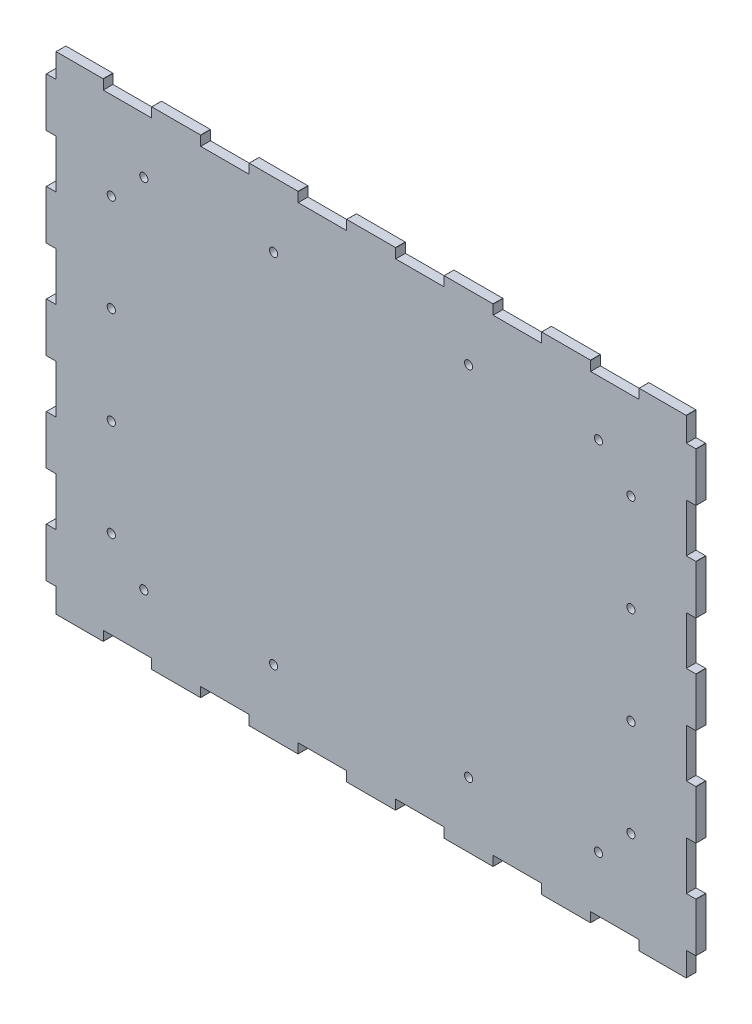
SolidWorks part; units mm, degrees
ref_plane "Front Plane" through (0, 0, 0) normal (0, 0, 1) x (1, 0, 0)
ref_plane "Top Plane" through (0, 0, 0) normal (0, 1, 0) x (1, 0, 0)
ref_plane "Right Plane" through (0, 0, 0) normal (1, 0, 0) x (0, 0, -1)
sketch "Model" plane through (0, 0, 0) normal (0, 0, 1) x (1, 0, 0)
  line L0 (-137.44, -124.95) -> (-137.43, -124.94)
  line L1 (-137.43, -124.94) -> (-137.42, -124.92)
  line L2 (-137.42, -124.92) -> (-137.41, -124.91)
  line L3 (-137.41, -124.91) -> (-137.4, -124.89)
  line L4 (-137.4, -124.89) -> (-137.4, -119.97)
  line L5 (-137.4, -119.97) -> (-112.6, -119.97)
  line L6 (-112.6, -119.97) -> (-112.6, -124.89)
  line L7 (-112.6, -124.89) -> (-112.58, -124.93)
  line L8 (-112.58, -124.93) -> (-112.57, -124.94)
  line L9 (-112.57, -124.94) -> (-112.55, -124.95)
  line L10 (-112.55, -124.95) -> (-112.54, -124.96)
  line L11 (-112.54, -124.96) -> (-112.52, -124.97)
  line L12 (-112.52, -124.97) -> (-87.48, -124.97)
  line L13 (-87.48, -124.97) -> (-87.44, -124.95)
  line L14 (-87.44, -124.95) -> (-87.43, -124.94)
  line L15 (-87.43, -124.94) -> (-87.42, -124.92)
  line L16 (-87.42, -124.92) -> (-87.41, -124.91)
  line L17 (-87.41, -124.91) -> (-87.4, -124.89)
  line L18 (-87.4, -124.89) -> (-87.4, -119.97)
  line L19 (-87.4, -119.97) -> (-62.6, -119.97)
  line L20 (-62.6, -119.97) -> (-62.6, -124.89)
  line L21 (-62.6, -124.89) -> (-62.58, -124.93)
  line L22 (-62.58, -124.93) -> (-62.57, -124.94)
  line L23 (-62.57, -124.94) -> (-62.55, -124.95)
  line L24 (-62.55, -124.95) -> (-62.54, -124.96)
  line L25 (-62.54, -124.96) -> (-62.52, -124.97)
  line L26 (-62.52, -124.97) -> (-37.48, -124.97)
  line L27 (-37.48, -124.97) -> (-37.44, -124.95)
  line L28 (-37.44, -124.95) -> (-37.43, -124.94)
  line L29 (-37.43, -124.94) -> (-37.42, -124.92)
  line L30 (-37.42, -124.92) -> (-37.41, -124.91)
  line L31 (-37.41, -124.91) -> (-37.4, -124.89)
  line L32 (-37.4, -124.89) -> (-37.4, -119.97)
  line L33 (-37.4, -119.97) -> (-12.6, -119.97)
  line L34 (-12.6, -119.97) -> (-12.6, -124.89)
  line L35 (-12.6, -124.89) -> (-12.58, -124.93)
  line L36 (-12.58, -124.93) -> (-12.57, -124.94)
  line L37 (-12.57, -124.94) -> (-12.55, -124.95)
  line L38 (-12.55, -124.95) -> (-12.54, -124.96)
  line L39 (-12.54, -124.96) -> (-12.52, -124.97)
  line L40 (-12.52, -124.97) -> (12.52, -124.97)
  line L41 (12.52, -124.97) -> (12.56, -124.95)
  line L42 (12.56, -124.95) -> (12.57, -124.94)
  line L43 (12.57, -124.94) -> (12.58, -124.92)
  line L44 (12.58, -124.92) -> (12.59, -124.91)
  line L45 (12.59, -124.91) -> (12.6, -124.89)
  line L46 (12.6, -124.89) -> (12.6, -119.97)
  line L47 (12.6, -119.97) -> (37.4, -119.97)
  line L48 (37.4, -119.97) -> (37.4, -124.89)
  line L49 (37.4, -124.89) -> (37.42, -124.93)
  line L50 (37.42, -124.93) -> (37.43, -124.94)
  line L51 (37.43, -124.94) -> (37.45, -124.95)
  line L52 (37.45, -124.95) -> (37.46, -124.96)
  line L53 (37.46, -124.96) -> (37.48, -124.97)
  line L54 (37.48, -124.97) -> (62.52, -124.97)
  line L55 (62.52, -124.97) -> (62.56, -124.95)
  line L56 (62.56, -124.95) -> (62.57, -124.94)
  line L57 (62.57, -124.94) -> (62.58, -124.92)
  line L58 (62.58, -124.92) -> (62.59, -124.91)
  line L59 (62.59, -124.91) -> (62.6, -124.89)
  line L60 (62.6, -124.89) -> (62.6, -119.97)
  line L61 (62.6, -119.97) -> (87.4, -119.97)
  line L62 (87.4, -119.97) -> (87.4, -124.89)
  line L63 (87.4, -124.89) -> (87.42, -124.93)
  line L64 (87.42, -124.93) -> (87.43, -124.94)
  line L65 (87.43, -124.94) -> (87.45, -124.95)
  line L66 (87.45, -124.95) -> (87.46, -124.96)
  line L67 (87.46, -124.96) -> (87.48, -124.97)
  line L68 (87.48, -124.97) -> (112.52, -124.97)
  line L69 (112.52, -124.97) -> (112.56, -124.95)
  line L70 (112.56, -124.95) -> (112.57, -124.94)
  line L71 (112.57, -124.94) -> (112.58, -124.92)
  line L72 (112.58, -124.92) -> (112.59, -124.91)
  line L73 (112.59, -124.91) -> (112.6, -124.89)
  line L74 (112.6, -124.89) -> (112.6, -119.97)
  line L75 (112.6, -119.97) -> (137.4, -119.97)
  line L76 (137.4, -119.97) -> (137.4, -124.89)
  line L77 (137.4, -124.89) -> (137.42, -124.93)
  line L78 (137.42, -124.93) -> (137.43, -124.94)
  line L79 (137.43, -124.94) -> (137.45, -124.95)
  line L80 (137.45, -124.95) -> (137.46, -124.96)
  line L81 (137.46, -124.96) -> (137.48, -124.97)
  line L82 (137.48, -124.97) -> (161.56, -124.97)
  line L83 (161.56, -124.97) -> (161.6, -124.95)
  line L84 (161.6, -124.95) -> (161.61, -124.94)
  line L85 (161.61, -124.94) -> (161.62, -124.92)
  line L86 (161.62, -124.92) -> (161.63, -124.91)
  line L87 (161.63, -124.91) -> (161.64, -124.89)
  line L88 (161.64, -124.89) -> (161.64, -112.6)
  line L89 (161.64, -112.6) -> (166.56, -112.6)
  line L90 (166.56, -112.6) -> (166.6, -112.58)
  line L91 (166.6, -112.58) -> (166.61, -112.57)
  line L92 (166.61, -112.57) -> (166.62, -112.55)
  line L93 (166.62, -112.55) -> (166.63, -112.54)
  line L94 (166.63, -112.54) -> (166.64, -112.52)
  line L95 (166.64, -112.52) -> (166.64, -87.48)
  line L96 (166.64, -87.48) -> (166.62, -87.44)
  line L97 (166.62, -87.44) -> (166.61, -87.43)
  line L98 (166.61, -87.43) -> (166.59, -87.42)
  line L99 (166.59, -87.42) -> (166.58, -87.41)
  line L100 (166.58, -87.41) -> (166.56, -87.4)
  line L101 (166.56, -87.4) -> (161.64, -87.4)
  line L102 (161.64, -87.4) -> (161.64, -62.6)
  line L103 (161.64, -62.6) -> (166.56, -62.6)
  line L104 (166.56, -62.6) -> (166.6, -62.58)
  line L105 (166.6, -62.58) -> (166.61, -62.57)
  line L106 (166.61, -62.57) -> (166.62, -62.55)
  line L107 (166.62, -62.55) -> (166.63, -62.54)
  line L108 (166.63, -62.54) -> (166.64, -62.52)
  line L109 (166.64, -62.52) -> (166.64, -37.48)
  line L110 (166.64, -37.48) -> (166.62, -37.44)
  line L111 (166.62, -37.44) -> (166.61, -37.43)
  line L112 (166.61, -37.43) -> (166.59, -37.42)
  line L113 (166.59, -37.42) -> (166.58, -37.41)
  line L114 (166.58, -37.41) -> (166.56, -37.4)
  line L115 (166.56, -37.4) -> (161.64, -37.4)
  line L116 (161.64, -37.4) -> (161.64, -12.6)
  line L117 (161.64, -12.6) -> (166.56, -12.6)
  line L118 (166.56, -12.6) -> (166.6, -12.58)
  line L119 (166.6, -12.58) -> (166.61, -12.57)
  line L120 (166.61, -12.57) -> (166.62, -12.55)
  line L121 (166.62, -12.55) -> (166.63, -12.54)
  line L122 (166.63, -12.54) -> (166.64, -12.52)
  line L123 (166.64, -12.52) -> (166.64, 12.52)
  line L124 (166.64, 12.52) -> (166.62, 12.56)
  line L125 (166.62, 12.56) -> (166.61, 12.57)
  line L126 (166.61, 12.57) -> (166.59, 12.58)
  line L127 (166.59, 12.58) -> (166.58, 12.59)
  line L128 (166.58, 12.59) -> (166.56, 12.6)
  line L129 (166.56, 12.6) -> (161.64, 12.6)
  line L130 (161.64, 12.6) -> (161.64, 37.4)
  line L131 (161.64, 37.4) -> (166.56, 37.4)
  line L132 (166.56, 37.4) -> (166.6, 37.42)
  line L133 (166.6, 37.42) -> (166.61, 37.43)
  line L134 (166.61, 37.43) -> (166.62, 37.45)
  line L135 (166.62, 37.45) -> (166.63, 37.46)
  line L136 (166.63, 37.46) -> (166.64, 37.48)
  line L137 (166.64, 37.48) -> (166.64, 62.52)
  line L138 (166.64, 62.52) -> (166.62, 62.56)
  line L139 (166.62, 62.56) -> (166.61, 62.57)
  line L140 (166.61, 62.57) -> (166.59, 62.58)
  line L141 (166.59, 62.58) -> (166.58, 62.59)
  line L142 (166.58, 62.59) -> (166.56, 62.6)
  line L143 (166.56, 62.6) -> (161.64, 62.6)
  line L144 (161.64, 62.6) -> (161.64, 87.4)
  line L145 (161.64, 87.4) -> (166.56, 87.4)
  line L146 (166.56, 87.4) -> (166.6, 87.42)
  line L147 (166.6, 87.42) -> (166.61, 87.43)
  line L148 (166.61, 87.43) -> (166.62, 87.45)
  line L149 (166.62, 87.45) -> (166.63, 87.46)
  line L150 (166.63, 87.46) -> (166.64, 87.48)
  line L151 (166.64, 87.48) -> (166.64, 112.52)
  line L152 (166.64, 112.52) -> (166.62, 112.56)
  line L153 (166.62, 112.56) -> (166.61, 112.57)
  line L154 (166.61, 112.57) -> (166.59, 112.58)
  line L155 (166.59, 112.58) -> (166.58, 112.59)
  line L156 (166.58, 112.59) -> (166.56, 112.6)
  line L157 (166.56, 112.6) -> (161.64, 112.6)
  line L158 (161.64, 112.6) -> (161.64, 124.89)
  line L159 (161.64, 124.89) -> (161.62, 124.93)
  line L160 (161.62, 124.93) -> (161.61, 124.94)
  line L161 (161.61, 124.94) -> (161.59, 124.95)
  line L162 (161.59, 124.95) -> (161.58, 124.96)
  line L163 (161.58, 124.96) -> (161.56, 124.97)
  line L164 (161.56, 124.97) -> (137.48, 124.97)
  line L165 (137.48, 124.97) -> (137.44, 124.95)
  line L166 (137.44, 124.95) -> (137.43, 124.94)
  line L167 (137.43, 124.94) -> (137.42, 124.92)
  line L168 (137.42, 124.92) -> (137.41, 124.91)
  line L169 (137.41, 124.91) -> (137.4, 124.89)
  line L170 (137.4, 124.89) -> (137.4, 119.97)
  line L171 (137.4, 119.97) -> (112.6, 119.97)
  line L172 (112.6, 119.97) -> (112.6, 124.89)
  line L173 (112.6, 124.89) -> (112.58, 124.93)
  line L174 (112.58, 124.93) -> (112.57, 124.94)
  line L175 (112.57, 124.94) -> (112.55, 124.95)
  line L176 (112.55, 124.95) -> (112.54, 124.96)
  line L177 (112.54, 124.96) -> (112.52, 124.97)
  line L178 (112.52, 124.97) -> (87.48, 124.97)
  line L179 (87.48, 124.97) -> (87.44, 124.95)
  line L180 (87.44, 124.95) -> (87.43, 124.94)
  line L181 (87.43, 124.94) -> (87.42, 124.92)
  line L182 (87.42, 124.92) -> (87.41, 124.91)
  line L183 (87.41, 124.91) -> (87.4, 124.89)
  line L184 (87.4, 124.89) -> (87.4, 119.97)
  line L185 (87.4, 119.97) -> (62.6, 119.97)
  line L186 (62.6, 119.97) -> (62.6, 124.89)
  line L187 (62.6, 124.89) -> (62.58, 124.93)
  line L188 (62.58, 124.93) -> (62.57, 124.94)
  line L189 (62.57, 124.94) -> (62.55, 124.95)
  line L190 (62.55, 124.95) -> (62.54, 124.96)
  line L191 (62.54, 124.96) -> (62.52, 124.97)
  line L192 (62.52, 124.97) -> (37.48, 124.97)
  line L193 (37.48, 124.97) -> (37.44, 124.95)
  line L194 (37.44, 124.95) -> (37.43, 124.94)
  line L195 (37.43, 124.94) -> (37.42, 124.92)
  line L196 (37.42, 124.92) -> (37.41, 124.91)
  line L197 (37.41, 124.91) -> (37.4, 124.89)
  line L198 (37.4, 124.89) -> (37.4, 119.97)
  line L199 (37.4, 119.97) -> (12.6, 119.97)
  line L200 (12.6, 119.97) -> (12.6, 124.89)
  line L201 (12.6, 124.89) -> (12.58, 124.93)
  line L202 (12.58, 124.93) -> (12.57, 124.94)
  line L203 (12.57, 124.94) -> (12.55, 124.95)
  line L204 (12.55, 124.95) -> (12.54, 124.96)
  line L205 (12.54, 124.96) -> (12.52, 124.97)
  line L206 (12.52, 124.97) -> (-12.52, 124.97)
  line L207 (-12.52, 124.97) -> (-12.56, 124.95)
  line L208 (-12.56, 124.95) -> (-12.57, 124.94)
  line L209 (-12.57, 124.94) -> (-12.58, 124.92)
  line L210 (-12.58, 124.92) -> (-12.59, 124.91)
  line L211 (-12.59, 124.91) -> (-12.6, 124.89)
  line L212 (-12.6, 124.89) -> (-12.6, 119.97)
  line L213 (-12.6, 119.97) -> (-37.4, 119.97)
  line L214 (-37.4, 119.97) -> (-37.4, 124.89)
  line L215 (-37.4, 124.89) -> (-37.42, 124.93)
  line L216 (-37.42, 124.93) -> (-37.43, 124.94)
  line L217 (-37.43, 124.94) -> (-37.45, 124.95)
  line L218 (-37.45, 124.95) -> (-37.46, 124.96)
  line L219 (-37.46, 124.96) -> (-37.48, 124.97)
  line L220 (-37.48, 124.97) -> (-62.52, 124.97)
  line L221 (-62.52, 124.97) -> (-62.56, 124.95)
  line L222 (-62.56, 124.95) -> (-62.57, 124.94)
  line L223 (-62.57, 124.94) -> (-62.58, 124.92)
  line L224 (-62.58, 124.92) -> (-62.59, 124.91)
  line L225 (-62.59, 124.91) -> (-62.6, 124.89)
  line L226 (-62.6, 124.89) -> (-62.6, 119.97)
  line L227 (-62.6, 119.97) -> (-87.4, 119.97)
  line L228 (-87.4, 119.97) -> (-87.4, 124.89)
  line L229 (-87.4, 124.89) -> (-87.42, 124.93)
  line L230 (-87.42, 124.93) -> (-87.43, 124.94)
  line L231 (-87.43, 124.94) -> (-87.45, 124.95)
  line L232 (-87.45, 124.95) -> (-87.46, 124.96)
  line L233 (-87.46, 124.96) -> (-87.48, 124.97)
  line L234 (-87.48, 124.97) -> (-112.52, 124.97)
  line L235 (-112.52, 124.97) -> (-112.56, 124.95)
  line L236 (-112.56, 124.95) -> (-112.57, 124.94)
  line L237 (-112.57, 124.94) -> (-112.58, 124.92)
  line L238 (-112.58, 124.92) -> (-112.59, 124.91)
  line L239 (-112.59, 124.91) -> (-112.6, 124.89)
  line L240 (-112.6, 124.89) -> (-112.6, 119.97)
  line L241 (-112.6, 119.97) -> (-137.4, 119.97)
  line L242 (-137.4, 119.97) -> (-137.4, 124.89)
  line L243 (-137.4, 124.89) -> (-137.42, 124.93)
  line L244 (-137.42, 124.93) -> (-137.43, 124.94)
  line L245 (-137.43, 124.94) -> (-137.45, 124.95)
  line L246 (-137.45, 124.95) -> (-137.46, 124.96)
  line L247 (-137.46, 124.96) -> (-137.48, 124.97)
  line L248 (-137.48, 124.97) -> (-161.56, 124.97)
  line L249 (-161.56, 124.97) -> (-161.6, 124.95)
  line L250 (-161.6, 124.95) -> (-161.61, 124.94)
  line L251 (-161.61, 124.94) -> (-161.62, 124.92)
  line L252 (-161.62, 124.92) -> (-161.63, 124.91)
  line L253 (-161.63, 124.91) -> (-161.64, 124.89)
  line L254 (-161.64, 124.89) -> (-161.64, 112.6)
  line L255 (-161.64, 112.6) -> (-166.56, 112.6)
  line L256 (-166.56, 112.6) -> (-166.6, 112.58)
  line L257 (-166.6, 112.58) -> (-166.61, 112.57)
  line L258 (-166.61, 112.57) -> (-166.62, 112.55)
  line L259 (-166.62, 112.55) -> (-166.63, 112.54)
  line L260 (-166.63, 112.54) -> (-166.64, 112.52)
  line L261 (-166.64, 112.52) -> (-166.64, 87.48)
  line L262 (-166.64, 87.48) -> (-166.62, 87.44)
  line L263 (-166.62, 87.44) -> (-166.61, 87.43)
  line L264 (-166.61, 87.43) -> (-166.59, 87.42)
  line L265 (-166.59, 87.42) -> (-166.58, 87.41)
  line L266 (-166.58, 87.41) -> (-166.56, 87.4)
  line L267 (-166.56, 87.4) -> (-161.64, 87.4)
  line L268 (-161.64, 87.4) -> (-161.64, 62.6)
  line L269 (-161.64, 62.6) -> (-166.56, 62.6)
  line L270 (-166.56, 62.6) -> (-166.6, 62.58)
  line L271 (-166.6, 62.58) -> (-166.61, 62.57)
  line L272 (-166.61, 62.57) -> (-166.62, 62.55)
  line L273 (-166.62, 62.55) -> (-166.63, 62.54)
  line L274 (-166.63, 62.54) -> (-166.64, 62.52)
  line L275 (-166.64, 62.52) -> (-166.64, 37.48)
  line L276 (-166.64, 37.48) -> (-166.62, 37.44)
  line L277 (-166.62, 37.44) -> (-166.61, 37.43)
  line L278 (-166.61, 37.43) -> (-166.59, 37.42)
  line L279 (-166.59, 37.42) -> (-166.58, 37.41)
  line L280 (-166.58, 37.41) -> (-166.56, 37.4)
  line L281 (-166.56, 37.4) -> (-161.64, 37.4)
  line L282 (-161.64, 37.4) -> (-161.64, 12.6)
  line L283 (-161.64, 12.6) -> (-166.56, 12.6)
  line L284 (-166.56, 12.6) -> (-166.6, 12.58)
  line L285 (-166.6, 12.58) -> (-166.61, 12.57)
  line L286 (-166.61, 12.57) -> (-166.62, 12.55)
  line L287 (-166.62, 12.55) -> (-166.63, 12.54)
  line L288 (-166.63, 12.54) -> (-166.64, 12.52)
  line L289 (-166.64, 12.52) -> (-166.64, -12.52)
  line L290 (-166.64, -12.52) -> (-166.62, -12.56)
  line L291 (-166.62, -12.56) -> (-166.61, -12.57)
  line L292 (-166.61, -12.57) -> (-166.59, -12.58)
  line L293 (-166.59, -12.58) -> (-166.58, -12.59)
  line L294 (-166.58, -12.59) -> (-166.56, -12.6)
  line L295 (-166.56, -12.6) -> (-161.64, -12.6)
  line L296 (-161.64, -12.6) -> (-161.64, -37.4)
  line L297 (-161.64, -37.4) -> (-166.56, -37.4)
  line L298 (-166.56, -37.4) -> (-166.6, -37.42)
  line L299 (-166.6, -37.42) -> (-166.61, -37.43)
  line L300 (-166.61, -37.43) -> (-166.62, -37.45)
  line L301 (-166.62, -37.45) -> (-166.63, -37.46)
  line L302 (-166.63, -37.46) -> (-166.64, -37.48)
  line L303 (-166.64, -37.48) -> (-166.64, -62.52)
  line L304 (-166.64, -62.52) -> (-166.62, -62.56)
  line L305 (-166.62, -62.56) -> (-166.61, -62.57)
  line L306 (-166.61, -62.57) -> (-166.59, -62.58)
  line L307 (-166.59, -62.58) -> (-166.58, -62.59)
  line L308 (-166.58, -62.59) -> (-166.56, -62.6)
  line L309 (-166.56, -62.6) -> (-161.64, -62.6)
  line L310 (-161.64, -62.6) -> (-161.64, -87.4)
  line L311 (-161.64, -87.4) -> (-166.56, -87.4)
  line L312 (-166.56, -87.4) -> (-166.6, -87.42)
  line L313 (-166.6, -87.42) -> (-166.61, -87.43)
  line L314 (-166.61, -87.43) -> (-166.62, -87.45)
  line L315 (-166.62, -87.45) -> (-166.63, -87.46)
  line L316 (-166.63, -87.46) -> (-166.64, -87.48)
  line L317 (-166.64, -87.48) -> (-166.64, -112.52)
  line L318 (-166.64, -112.52) -> (-166.62, -112.56)
  line L319 (-166.62, -112.56) -> (-166.61, -112.57)
  line L320 (-166.61, -112.57) -> (-166.59, -112.58)
  line L321 (-166.59, -112.58) -> (-166.58, -112.59)
  line L322 (-166.58, -112.59) -> (-166.56, -112.6)
  line L323 (-166.56, -112.6) -> (-161.64, -112.6)
  line L324 (-161.64, -112.6) -> (-161.64, -124.89)
  line L325 (-161.64, -124.89) -> (-161.62, -124.93)
  line L326 (-161.62, -124.93) -> (-161.61, -124.94)
  line L327 (-161.61, -124.94) -> (-161.59, -124.95)
  line L328 (-161.59, -124.95) -> (-161.58, -124.96)
  line L329 (-161.58, -124.96) -> (-161.56, -124.97)
  line L330 (-161.56, -124.97) -> (-137.48, -124.97)
  line L331 (-137.48, -124.97) -> (-137.44, -124.95)
extrude "Boss-Extrude1" add sketch "Model" along normal blind 5
sketch "Sketch1" plane through (0, 0, 5) normal (0, 0, 1) x (1, 0, 0)
  line L0 (-149.9367, 58.27) -> (-149.9367, 108.27) construction
  line L1 (-166.5367, 124.87) -> (166.5367, 124.87) construction
  line L2 (-166.5367, 124.87) -> (-166.5367, -124.87) construction
  line L3 (-166.5367, -124.87) -> (166.5367, -124.87) construction
  line L4 (166.5367, 124.87) -> (166.5367, -124.87) construction
  line L5 (-166.5367, 124.87) -> (166.5367, -124.87) construction
  line L6 (-166.5367, -124.87) -> (166.5367, 124.87) construction
  line L7 (-149.9367, 108.27) -> (-99.9367, 108.27) construction
  line L8 (0, -124.87) -> (0, 124.87) construction
  line L9 (166.5367, 0) -> (-166.5367, 0) construction
  circle A0 centre (-116.6033, 91.6033) radius 2.1
  circle A1 centre (-133.27, 74.9367) radius 2.1
  circle A2 centre (133.27, 74.9367) radius 2.1
  circle A3 centre (116.6033, 91.6033) radius 2.1
  circle A4 centre (133.27, -74.9367) radius 2.1
  circle A5 centre (116.6033, -91.6033) radius 2.1
  circle A6 centre (-116.6033, -91.6033) radius 2.1
  circle A7 centre (-133.27, -74.9367) radius 2.1
  circle A8 centre (-50, 91.6033) radius 2.1
  circle A9 centre (50, 91.6033) radius 2.1
  circle A11 centre (50, -91.6033) radius 2.1
  circle A12 centre (-50, -91.6033) radius 2.1
  circle A13 centre (-133.27, 25) radius 2.1
  circle A14 centre (-133.27, -25) radius 2.1
  circle A16 centre (133.27, 25) radius 2.1
  circle A17 centre (133.27, -25) radius 2.1
  point P4 (0, 0)
  point P6 (0, 0)
  point P16 (-230.1917, 110.0399)
  point P17 (-106.8504, 91.6033)
  point P18 (-37.051, 91.6033)
  point P19 (0, 0)
  point P22 (0, 0)
  point P39 (0, 0)
  point P48 (-77.4249, 11.7656)
  point P49 (-210.7583, 37.0393)
  point P50 (-77.4249, 11.7656)
  point P51 (-77.4249, 11.7656)
  point P55 (-77.4249, 11.7656)
  dimension "D6" = 4.2
  dimension "D1" = 333.0733
  dimension "D2" = 249.74
  dimension "D3" = 16.6667
  dimension "D4" = 16.6667
  dimension "D5" = 16.6667
  dimension "D7" = 16.6667
  dimension "D8" = 16.6
  dimension "D9" = 16.6
  dimension "D10" = 50
  dimension "D11" = 100
  dimension "D12" = 50
extrude "Cut-Extrude1" cut sketch "Sketch1" against normal through all
